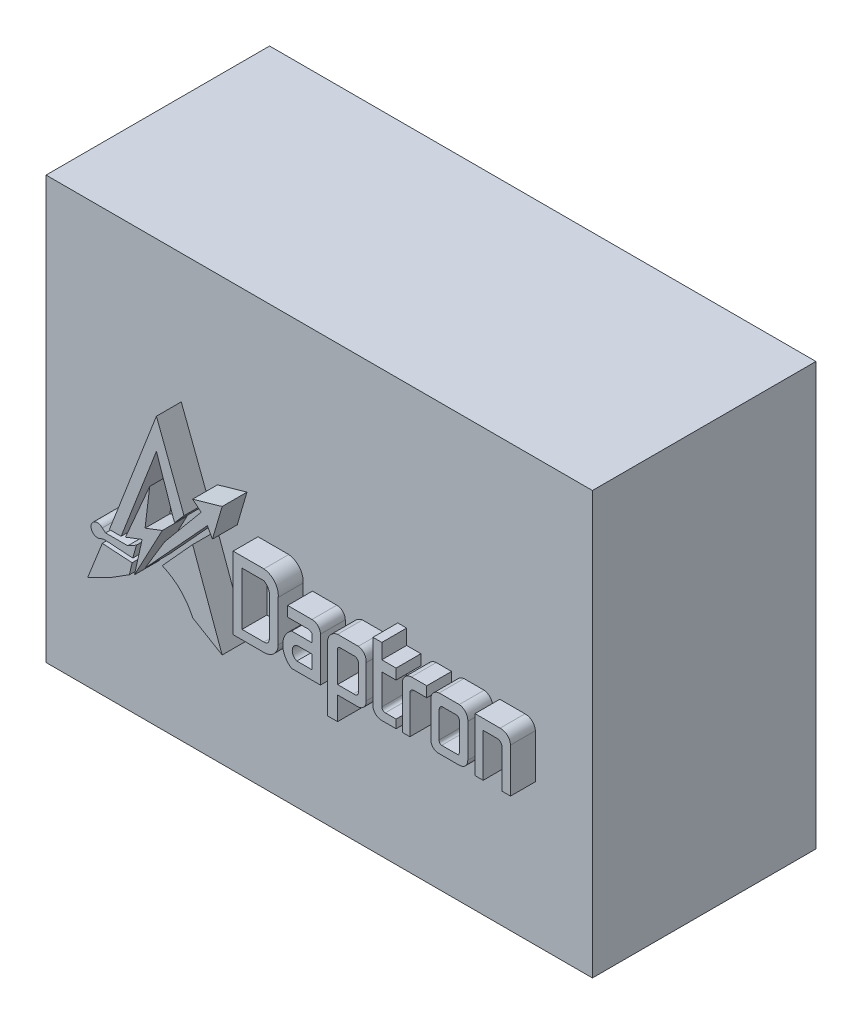
SolidWorks part; units mm, degrees
ref_plane "Plan de face" through (0, 0, 0) normal (0, 0, 1) x (1, 0, 0)
ref_plane "Plan de dessus" through (0, 0, 0) normal (0, 1, 0) x (1, 0, 0)
ref_plane "Plan de droite" through (0, 0, 0) normal (1, 0, 0) x (0, 0, -1)
sketch "Esquisse1" plane through (0, 0, 0) normal (0, 0, 1) x (1, 0, 0)
  line L0 (5.4437, 11.8125) -> (3.5501, 6.9145)
  line L1 (4.0235, 6.9145) -> (5.4437, 10.588)
  line L2 (5.4437, 10.588) -> (6.172, 8.4622)
  line L3 (6.172, 8.4622) -> (6.5544, 8.8992)
  line L4 (6.5544, 8.8992) -> (5.4437, 11.8125)
  line L5 (5.1732, 9.2299) -> (4.9873, 7.6806)
  line L6 (4.9873, 7.6806) -> (5.6782, 7.9441)
  line L7 (5.6782, 7.9441) -> (4.5601, 5.8391)
  line L8 (4.5601, 5.8391) -> (4.8687, 7.2278)
  line L9 (4.8687, 7.2278) -> (4.1993, 6.9726)
  line L10 (4.1993, 6.9726) -> (5.1732, 9.2299)
  line L11 (3.5501, 6.9145) -> (4.0235, 6.9145)
  line L12 (3.2657, 6.2899) -> (2.6779, 4.8081)
  line L13 (2.6779, 4.8081) -> (3.6336, 5.2865)
  line L14 (3.6336, 5.2865) -> (4.3555, 5.7388)
  line L15 (4.3555, 5.7388) -> (4.4646, 6.2138)
  line L16 (4.4646, 6.2138) -> (3.2657, 6.2899)
  line L17 (6.9026, 8.0655) -> (8.0904, 4.8081)
  line L18 (8.0904, 4.8081) -> (6.9026, 5.5126)
  line L19 (6.9026, 8.0655) -> (5.6782, 6.7185)
  line L20 (4.9873, 6.2899) -> (5.776, 7.6001)
  line L21 (5.776, 7.6001) -> (7.2455, 9.3635)
  line L22 (7.2455, 9.3635) -> (6.9026, 9.6492)
  line L23 (6.9026, 9.6492) -> (8.0904, 9.988)
  line L24 (8.0904, 9.988) -> (7.6986, 8.6533)
  line L25 (7.6986, 8.6533) -> (7.4965, 9.0233)
  line L26 (7.4965, 9.0233) -> (4.9873, 6.2899)
  line L27 (3.2657, 6.825) -> (3.3964, 6.7185)
  line L28 (3.3964, 6.7185) -> (4.2913, 6.7185)
  line L29 (4.2913, 6.7185) -> (4.64, 6.9145)
  line L30 (4.64, 6.9145) -> (4.4928, 6.3893)
  line L31 (4.4928, 6.3893) -> (3.3442, 6.4633)
  line L32 (3.3442, 6.4633) -> (3.205, 6.4263)
  line L33 (8.5331, 8.6533) -> (8.5331, 5.7388)
  line L34 (8.5331, 5.7388) -> (9.7727, 5.7388)
  line L35 (8.5331, 8.6533) -> (9.7727, 8.6533)
  line L36 (8.8924, 8.2405) -> (8.8924, 6.1026)
  line L37 (8.8924, 6.1026) -> (9.7727, 6.1026)
  line L38 (8.8924, 8.2405) -> (9.7727, 8.2405)
  line L39 (9.9882, 7.9441) -> (9.9882, 6.2899)
  line L40 (10.3475, 7.9441) -> (10.3475, 6.2899)
  line L41 (10.7271, 7.8551) -> (11.7075, 7.8551)
  line L42 (12.048, 7.5147) -> (12.048, 5.7387)
  line L43 (12.048, 5.7387) -> (10.8884, 5.7387)
  line L44 (10.8884, 7.0431) -> (11.7052, 7.0431)
  line L45 (11.7052, 7.0431) -> (11.7052, 7.3658)
  line L46 (10.7271, 7.8551) -> (10.7271, 7.4465)
  line L47 (10.7271, 7.4465) -> (11.4682, 7.4465)
  line L48 (11.0976, 6.6507) -> (11.7052, 6.6507)
  line L49 (11.7052, 6.6507) -> (11.7052, 6.1026)
  line L50 (11.7052, 6.1026) -> (11.0976, 6.1026)
  line L51 (12.739, 7.2959) -> (12.739, 6.1026)
  line L52 (12.739, 6.1026) -> (13.385, 6.1026)
  line L53 (12.817, 7.4357) -> (13.385, 7.4357)
  line L54 (13.5744, 7.2959) -> (13.5744, 6.2138)
  line L55 (13.8863, 7.4357) -> (13.8863, 6.1026)
  line L56 (12.739, 5.7387) -> (12.739, 4.8081)
  line L57 (12.739, 5.7387) -> (13.5744, 5.7387)
  line L58 (12.739, 4.8081) -> (12.338, 4.8081)
  line L59 (12.338, 4.8081) -> (12.338, 7.2959)
  line L60 (12.739, 7.8551) -> (13.5744, 7.8551)
  line L61 (14.1612, 8.4622) -> (14.1612, 6.0766)
  line L62 (14.1612, 8.4622) -> (14.5189, 8.4622)
  line L63 (14.5189, 8.4622) -> (14.5189, 7.8551)
  line L64 (14.5189, 7.8551) -> (15.0937, 7.8551)
  line L65 (15.0937, 7.8551) -> (15.0937, 7.4357)
  line L66 (15.0937, 7.4357) -> (14.5189, 7.4357)
  line L67 (14.5189, 7.4357) -> (14.5189, 6.2138)
  line L68 (14.5189, 5.7387) -> (15.0937, 5.7387)
  line L69 (15.0937, 5.7387) -> (15.0937, 6.0766)
  line L70 (15.0937, 6.0766) -> (14.6594, 6.0766)
  line L71 (15.3458, 7.4357) -> (15.3458, 5.7387)
  line L72 (15.3458, 5.7387) -> (15.6515, 5.7387)
  line L73 (15.6515, 5.7387) -> (15.6515, 7.2712)
  line L74 (15.8117, 7.4357) -> (16.3286, 7.4357)
  line L75 (16.3286, 7.4357) -> (16.3286, 7.8551)
  line L76 (16.3286, 7.8551) -> (15.7098, 7.8551)
  line L78 (16.9298, 7.4357) -> (17.5373, 7.4357)
  line L81 (17.9803, 7.4357) -> (17.9803, 6.0785)
  line L82 (16.8285, 5.7387) -> (17.6405, 5.7387)
  line L83 (16.4945, 7.4357) -> (16.4945, 6.0271)
  line L84 (16.8285, 7.8551) -> (17.6386, 7.8551)
  line L85 (16.8285, 7.2734) -> (16.8285, 6.2155)
  line L86 (17.6386, 7.2734) -> (17.6386, 6.2155)
  line L87 (16.9298, 6.0785) -> (17.5997, 6.0785)
  line L88 (18.6011, 7.4357) -> (18.6011, 5.6941)
  line L89 (18.6011, 5.6941) -> (18.2707, 5.6941)
  line L90 (18.2707, 5.6941) -> (18.2707, 7.8551)
  line L91 (18.2707, 7.8551) -> (19.2838, 7.8551)
  line L92 (19.7022, 7.4745) -> (19.7022, 5.6941)
  line L93 (19.7022, 5.6941) -> (19.3572, 5.6941)
  line L94 (19.3572, 5.6941) -> (19.3572, 7.1838)
  line L95 (18.6011, 5.6941) -> (18.6011, 7.4357)
  line L96 (18.6011, 7.4357) -> (19.1957, 7.4357)
  line L98 (0, 17.0155) -> (22, 17.0155)
  line L99 (0, 17.0155) -> (0, 0.0155)
  line L100 (0, 0.0155) -> (22, 0.0155)
  line L101 (22, 17.0155) -> (22, 0.0155)
  arc A0 (5.6782, 6.7185) -> (6.9026, 5.5126) centre (4.7991, 4.6013) cw
  circle A1 centre (3.0709, 6.6507) radius 0.1
  arc A2 (3.2657, 6.825) -> (3.205, 6.4263) centre (3.0709, 6.6507) ccw
  arc A3 (9.7727, 8.6533) -> (10.3475, 7.9441) centre (9.7055, 8.0112) cw
  arc A4 (9.7727, 8.2405) -> (9.9882, 7.9441) centre (9.5544, 7.8551) cw
  arc A5 (9.7727, 6.1026) -> (9.9882, 6.2899) centre (9.7868, 6.304) ccw
  arc A6 (9.7727, 5.7388) -> (10.3475, 6.2899) centre (9.7846, 6.3018) ccw
  arc A7 (11.0976, 6.6507) -> (11.0976, 6.1026) centre (11.208, 6.3767) ccw
  arc A8 (10.8884, 7.0431) -> (10.8884, 5.7387) centre (11.3038, 6.3909) ccw
  arc A9 (11.7075, 7.8551) -> (12.048, 7.5147) centre (11.7075, 7.5147) cw
  arc A10 (11.4682, 7.4465) -> (11.7052, 7.3658) centre (11.511, 7.1838) cw
  arc A11 (13.5744, 7.8551) -> (13.8863, 7.4357) centre (13.5206, 7.4895) cw
  arc A12 (12.739, 7.8551) -> (12.338, 7.2959) centre (12.8181, 7.375) ccw
  arc A13 (12.739, 7.2959) -> (12.817, 7.4357) centre (12.8479, 7.3268) cw
  arc A14 (13.385, 7.4357) -> (13.5744, 7.2959) centre (13.4098, 7.2712) cw
  arc A15 (13.5744, 6.2138) -> (13.385, 6.1026) centre (13.4241, 6.2529) cw
  arc A16 (13.8863, 6.1026) -> (13.5744, 5.7387) centre (13.5483, 6.0766) cw
  arc A17 (14.5189, 6.2138) -> (14.6594, 6.0766) centre (14.6578, 6.2155) ccw
  arc A18 (14.1612, 6.0766) -> (14.5189, 5.7387) centre (14.509, 6.0865) ccw
  arc A19 (15.3458, 7.4357) -> (15.7098, 7.8551) centre (15.7375, 7.4634) cw
  arc A20 (15.8117, 7.4357) -> (15.6515, 7.2712) centre (15.8139, 7.2734) ccw
  arc A21 (16.8285, 7.8551) -> (16.4945, 7.4357) centre (16.8712, 7.4784) ccw
  arc A22 (17.6386, 7.8551) -> (17.9803, 7.4357) centre (17.5997, 7.4745) cw
  arc A23 (17.9803, 6.0785) -> (17.6405, 5.7387) centre (17.6405, 6.0785) cw
  arc A24 (16.4945, 6.0271) -> (16.8285, 5.7387) centre (16.8057, 6.0499) ccw
  arc A27 (17.5373, 7.4357) -> (17.6386, 7.2734) centre (17.5068, 7.3039) cw
  arc A28 (16.8285, 7.2734) -> (16.9298, 7.4357) centre (17.018, 7.268) cw
  arc A29 (16.8285, 6.2155) -> (16.9298, 6.0785) centre (16.9476, 6.1976) ccw
  arc A30 (17.6386, 6.2155) -> (17.5997, 6.0785) centre (17.4659, 6.1904) cw
  arc A31 (19.1957, 7.4357) -> (19.3572, 7.1838) centre (19.1505, 7.229) cw
  arc A32 (19.2838, 7.8551) -> (19.7022, 7.4745) centre (19.3027, 7.4556) cw
  point P158 (0, 0)
  dimension "D1" = 22
  dimension "D2" = 17
extrude "Boss.-Extru.1" add sketch "Esquisse1" along normal blind 10 contours L0 L11 L1 L2 L3 L4 | L19 A0 L18 L17 | L26 L25 L24 L23 L22 L21 L20 | A32 L91 L90 L89 L88 L96 A31 L94 L93 L92 | L83 A24 L82 A23 L81 A22 L84 A21 L86 A30 L87 A29 L85 A28 L78 A27 | A20 L74 L75 L76 A19 L71 L72 L73 | L61 A18 L68 L69 L70 A17 L67 L66 L65 L64 L63 L62 | A16 L55 A11 L60 A12 L59 L58 L56 L57 L54 A15 L52 L51 A13 L53 A14 | L47 A10 L45 L44 A8 L43 L42 A9 L41 L46 A7 L48 L49 L50 | L34 A6 L40 A3 L35 L33 A5 L37 L36 L38 A4 L39 | L15 L16 L12 L13 L14 | L10 L5 L6 L7 L8 L9 | L31 L32 A2 L27 L28 L29 L30
sketch "Esquisse2" plane through (0, 0, 0) normal (0, 0, 1) x (1, 0, 0)
  line L1 (0, 0) -> (22, 0)
  line L2 (0, 0) -> (0, 17)
  line L3 (0, 17) -> (22, 17)
  line L4 (22, 0) -> (22, 17)
  dimension "D1" = 22
  dimension "D2" = 17
extrude "Boss.-Extru.2" add sketch "Esquisse2" along normal blind 9
